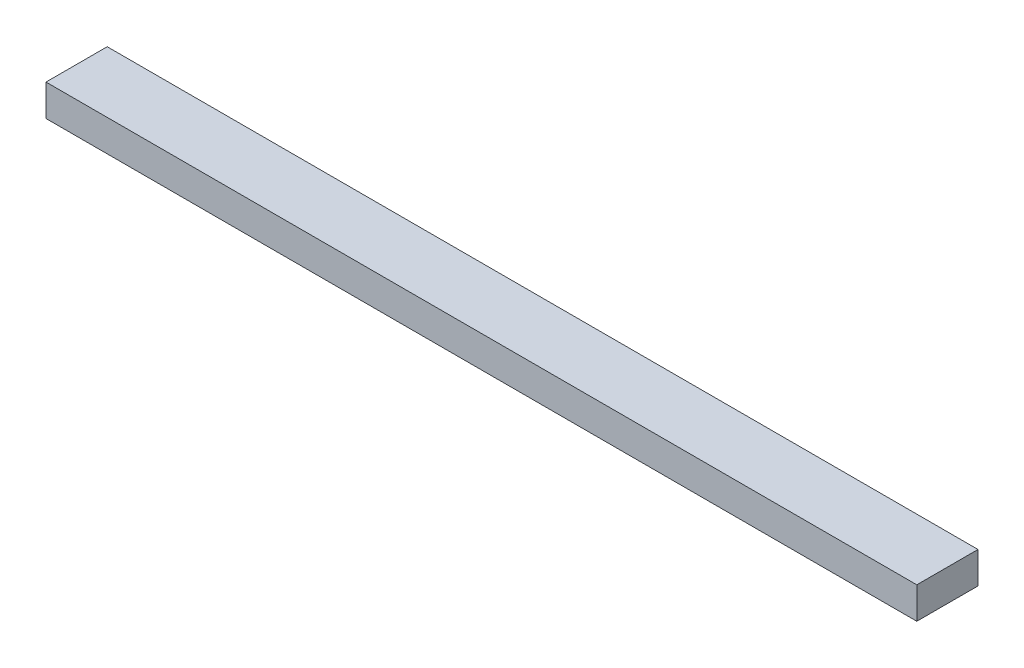
SolidWorks part; units mm, degrees
ref_plane "Plan de face" through (0, 0, 0) normal (0, 0, 1) x (1, 0, 0)
ref_plane "Plan de dessus" through (0, 0, 0) normal (0, 1, 0) x (1, 0, 0)
ref_plane "Plan de droite" through (0, 0, 0) normal (1, 0, 0) x (0, 0, -1)
sketch "Esquisse1" plane through (0, 0, 0) normal (0, 1, 0) x (1, 0, 0)
  line L0 (-87.5, 0) -> (0, 0) construction
  line L1 (-87.5, 6.15) -> (87.5, 6.15)
  line L2 (-87.5, 6.15) -> (-87.5, -6.15)
  line L3 (-87.5, -6.15) -> (87.5, -6.15)
  line L4 (87.5, 6.15) -> (87.5, -6.15)
  line L5 (0, 0) -> (87.5, 0) construction
  dimension "D1" = 12.3
  dimension "D2" = 175
extrude "Boss.-Extru.1" add sketch "Esquisse1" along normal blind 6.35
